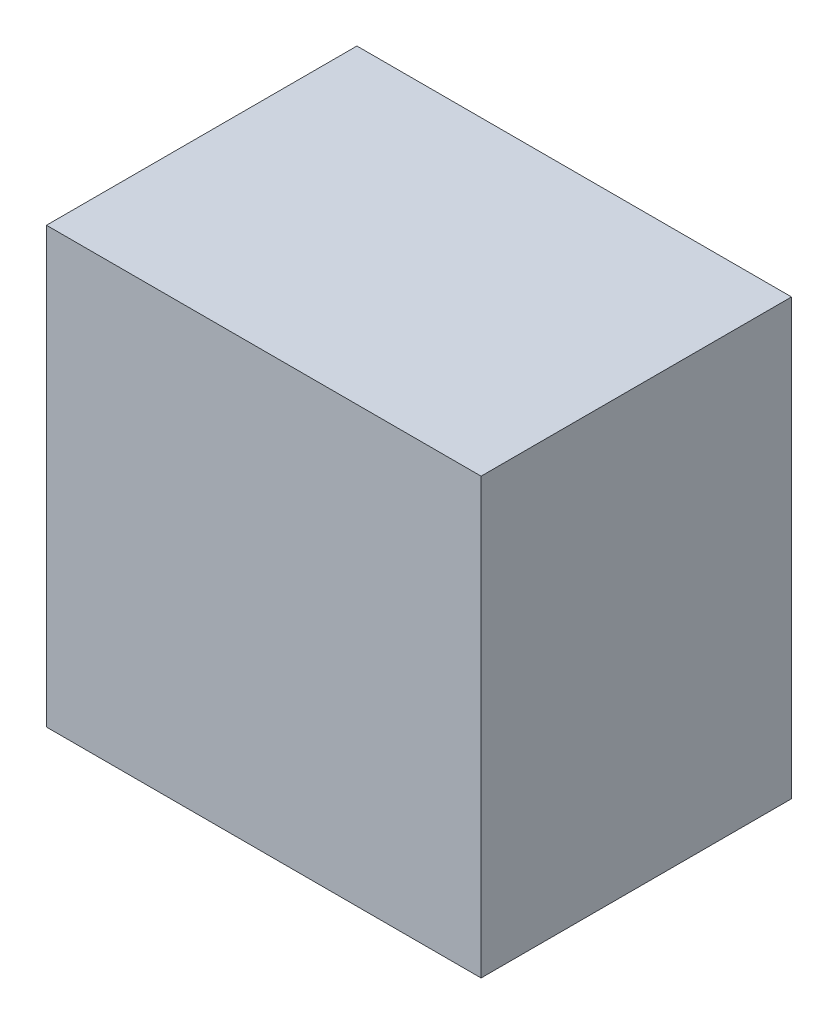
SolidWorks part; units mm, degrees
ref_plane "Front Plane" through (0, 0, 0) normal (0, 0, 1) x (1, 0, 0)
ref_plane "Top Plane" through (0, 0, 0) normal (0, 1, 0) x (1, 0, 0)
ref_plane "Right Plane" through (0, 0, 0) normal (1, 0, 0) x (0, 0, -1)
other "Configuration Table"
sketch "Sketch1" plane through (0, 0, 0) normal (0, 0, 1) x (1, 0, 0)
  line L1 (-28, 142) -> (28, 142)
  line L2 (-28, 142) -> (-28, 198)
  line L3 (-28, 198) -> (28, 198)
  line L4 (28, 142) -> (28, 198)
extrude "SM_motor_tarak_57x57x40_1" add sketch "Sketch1" against normal blind 40 from offset 740 separate body
